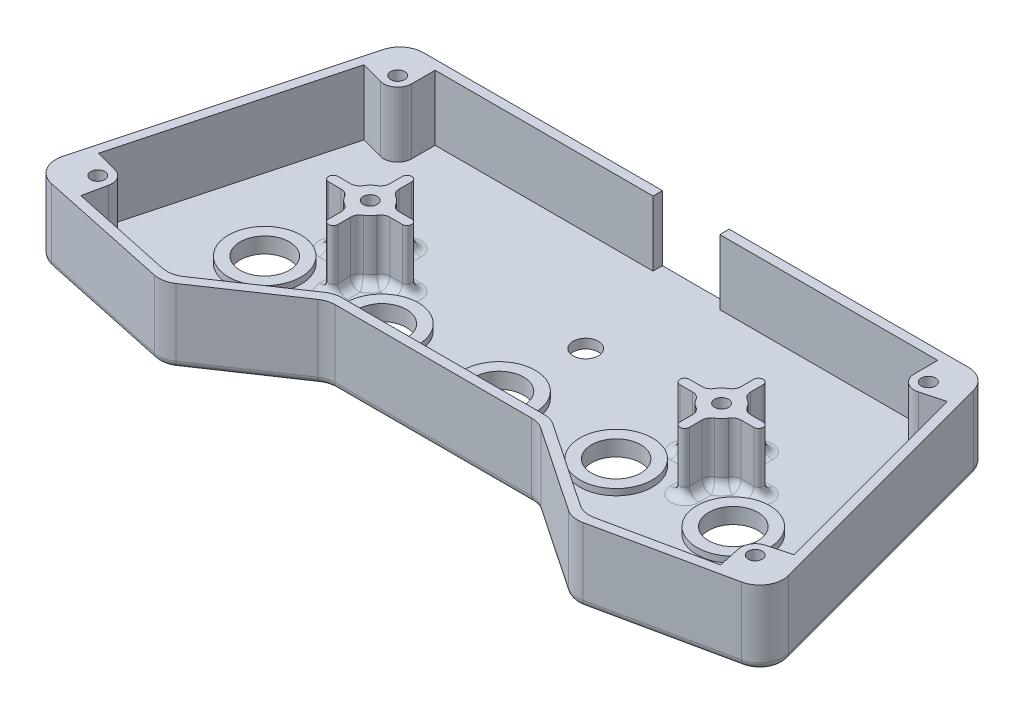
SolidWorks part; units mm, degrees
ref_plane "Front Plane" through (0, 0, 0) normal (0, 0, 1) x (1, 0, 0)
ref_plane "Top Plane" through (0, 0, 0) normal (0, 1, 0) x (1, 0, 0)
ref_plane "Right Plane" through (0, 0, 0) normal (1, 0, 0) x (0, 0, -1)
sketch "Sketch10" plane through (0, 0, 0) normal (0, 1, 0) x (1, 0, 0)
  line L0 (62, 32) -> (-62, 32)
  line L1 (-62, 32) -> (-78.8232, -30.7852)
  line L2 (-78.8232, -30.7852) -> (-43.6451, -38.2625)
  line L3 (-43.6451, -38.2625) -> (-22.5, -24)
  line L4 (-22.5, -24) -> (22.5, -24)
  line L5 (22.5, -24) -> (43.6451, -38.2625)
  line L6 (43.6451, -38.2625) -> (78.8232, -30.7852)
  line L7 (78.8232, -30.7852) -> (62, 32)
  line L8 (-50, -10) -> (-25, -10) construction
  line L9 (-25, -10) -> (0, -10) construction
  line L10 (0, -10) -> (25, -10) construction
  line L11 (25, -10) -> (50, -10) construction
  line L12 (-27, 0) -> (27, 0) construction
  line L13 (0, 0) -> (0, 32) construction
  line L14 (0, 0) -> (0, -24) construction
  line L15 (78.8232, -30.7852) -> (22.5, -24) construction
  line L16 (-22.5, -24) -> (-78.8232, -30.7852) construction
  circle A0 centre (50, -10) radius 5.25
  circle A2 centre (0, -10) radius 5.25
  circle A3 centre (25, -10) radius 5.25
  circle A5 centre (-50, -10) radius 5.25
  circle A6 centre (-25, -10) radius 5.25
  dimension "D1" = 10.5
  dimension "D2" = 25
  dimension "D3" = 65
  dimension "D4" = 124
  dimension "D5" = 10
  dimension "D6" = 105
  dimension "D7" = 56
  dimension "D8" = 45
  dimension "D9" = 32
  dimension "D10" = 34
  dimension "D11" = 12
extrude "Boss-Extrude5" add sketch "Sketch10" along normal blind 2 separate body contours L7 L0 L1 L2 L3 L4 L5 L6
sketch "Sketch11" plane through (0, 2, 0) normal (0, 1, 0) x (1, 0, 0)
  line L0 (-78.8232, -30.7852) -> (-62, 32)
  line L1 (-62, 32) -> (62, 32)
  line L2 (62, 32) -> (78.8232, -30.7852)
  line L3 (78.8232, -30.7852) -> (43.6451, -38.2625)
  line L4 (43.6451, -38.2625) -> (22.5, -24)
  line L5 (22.5, -24) -> (-22.5, -24)
  line L6 (-22.5, -24) -> (-43.6451, -38.2625)
  line L7 (-43.6451, -38.2625) -> (-78.8232, -30.7852)
  line L8 (-44.0596, -36.1297) -> (-76.3459, -29.2671)
  line L9 (-76.3459, -29.2671) -> (-60.4653, 30)
  line L10 (-60.4653, 30) -> (60.4653, 30)
  line L11 (60.4653, 30) -> (76.3459, -29.2671)
  line L12 (76.3459, -29.2671) -> (44.0596, -36.1297)
  line L13 (44.0596, -36.1297) -> (23.1115, -22)
  line L14 (23.1115, -22) -> (-23.1115, -22)
  line L15 (-23.1115, -22) -> (-44.0596, -36.1297)
  dimension "D1" = 2
extrude "Boss-Extrude7" add sketch "Sketch11" along direction (0, -1, 0) on the side of the normal offset from surface (13.875 mm away) 15.875 contours L0 L1 L2 L3 L4 L5 L6 L7
fillet "Fillet4" radius 5 16 edges at (62, 7.9375, -32) (78.8232, 7.9375, 30.7852) (43.6451, 7.9375, 38.2625) (22.5, 7.9375, 24) (-22.5, 7.9375, 24) (-43.6451, 7.9375, 38.2625) (-62, 7.9375, -32) (-78.8232, 7.9375, 30.7852) (76.3459, 8.9375, 29.2671) (60.4653, 8.9375, -30) (44.0596, 8.9375, 36.1297) (23.1115, 8.9375, 22) (-23.1115, 8.9375, 22) (-44.0596, 8.9375, 36.1297) (-76.3459, 8.9375, 29.2671) (-60.4653, 8.9375, -30)
fillet "Fillet5" radius 1.5 16 edges at (43.7275, 0, 37.8387) (32.8264, 0, 30.9653) (22.4332, 0, 24.2185) (0, 0, 24) (-22.4332, 0, 24.2185) (-32.8264, 0, 30.9653) (-43.7275, 0, 37.8387) (-59.6953, 0, 34.851) (-76.8931, 0, 29.6024) (-70.2263, 0, -1.2991) (-61.2072, 0, -30.9668) (0, 0, -32) (61.2072, 0, -30.9668) (70.2263, 0, -1.2991) (76.8931, 0, 29.6024) (59.6953, 0, 34.851)
sketch "Sketch12" plane through (0, 2, 0) normal (0, 1, 0) x (1, 0, 0)
  line L0 (-62.2348, 23.3963) -> (-57.4052, 22.1022)
  line L1 (-61.4583, 26.2941) -> (-74.9822, -24.1777) construction
  line L2 (-53.6287, 25) -> (-53.6287, 30)
  line L3 (56.6287, 30) -> (-56.6287, 30) construction
  line L4 (-53.6287, 30) -> (-56.6287, 30)
  line L5 (-61.4583, 26.2941) -> (-62.2348, 23.3963)
  line L6 (-74.9822, -24.1777) -> (-74.2058, -21.2799)
  line L7 (-74.2058, -21.2799) -> (-69.3761, -22.574)
  line L8 (-67.2181, -26.0955) -> (-68.2577, -30.9863)
  line L9 (-71.1921, -30.3625) -> (-46.1356, -35.6885) construction
  line L10 (-68.2577, -30.9863) -> (-71.1921, -30.3625)
  line L11 (0, 0) -> (0, 17.9434) construction
  line L12 (68.2577, -30.9863) -> (71.1921, -30.3625)
  line L13 (67.2181, -26.0955) -> (68.2577, -30.9863)
  line L14 (74.2058, -21.2799) -> (69.3761, -22.574)
  line L15 (74.9822, -24.1777) -> (74.2058, -21.2799)
  line L16 (61.4583, 26.2941) -> (62.2348, 23.3963)
  line L17 (53.6287, 30) -> (56.6287, 30)
  line L18 (53.6287, 25) -> (53.6287, 30)
  line L19 (62.2348, 23.3963) -> (57.4052, 22.1022)
  arc A0 (-57.4052, 22.1022) -> (-53.6287, 25) centre (-56.6287, 25) ccw
  arc A1 (-56.6287, 30) -> (-61.4583, 26.2941) centre (-56.6287, 25) ccw
  arc A2 (-69.3761, -22.574) -> (-67.2181, -26.0955) centre (-70.1526, -25.4718) cw
  arc A3 (-71.1921, -30.3625) -> (-74.9822, -24.1777) centre (-70.1526, -25.4718) cw
  circle A4 centre (-56.6287, 25) radius 1.5
  circle A5 centre (-70.1526, -25.4718) radius 1.5
  circle A6 centre (70.1526, -25.4718) radius 1.5
  circle A7 centre (56.6287, 25) radius 1.5
  arc A8 (71.1921, -30.3625) -> (74.9822, -24.1777) centre (70.1526, -25.4718) ccw
  arc A9 (69.3761, -22.574) -> (67.2181, -26.0955) centre (70.1526, -25.4718) ccw
  arc A10 (56.6287, 30) -> (61.4583, 26.2941) centre (56.6287, 25) cw
  arc A11 (57.4052, 22.1022) -> (53.6287, 25) centre (56.6287, 25) cw
  dimension "D1" = 3
  dimension "D2" = 1.5
extrude "Boss-Extrude8" add sketch "Sketch12" along normal up to surface (13.875 mm away) contours L0 A0 L2 L4 A1 L5
sketch "Sketch14" plane through (0, 0, -30) normal (0, 0, 1) x (1, 0, 0)
  line L0 (-53.6287, 15.875) -> (53.6287, 15.875) construction
  line L5 (0, 0) -> (0, 15.875) construction
  line L10 (-6.625, 15.03) -> (-6.625, 2.5) construction
  line L11 (-7.125, 15.875) -> (7.125, 15.875)
  line L12 (-7.125, 15.875) -> (-7.125, 2)
  line L13 (-7.125, 2) -> (7.125, 2)
  line L14 (7.125, 15.875) -> (7.125, 2)
  line L15 (53.6287, 2) -> (-53.6287, 2) construction
  dimension "D1" = 0.5
extrude "Cut-Extrude2" cut sketch "Sketch14" against normal through all
sketch "Sketch15" plane through (0, 0, 0) normal (0, -1, 0) x (1, 0, 0)
  line L0 (0, -8.5) -> (0, -30.5) construction
  line L1 (-58.1634, -30.5) -> (58.1634, -30.5) construction
  circle A0 centre (0, -8.5) radius 2.7
  dimension "D2" = 5.4
  dimension "D1" = 22
extrude "Cut-Extrude3" cut sketch "Sketch15" against normal through all contours A0
sketch "Sketch16" plane through (0, 2, 0) normal (0, 1, 0) x (1, 0, 0)
  circle A0 centre (25, -10) radius 7.75
  circle A1 centre (25, -10) radius 5.25
  circle A2 centre (0, -10) radius 7.75
  circle A3 centre (0, -10) radius 5.25
  circle A4 centre (-50, -10) radius 5.25
  circle A5 centre (-50, -10) radius 7.75
  circle A6 centre (-25, -10) radius 5.25
  circle A7 centre (-25, -10) radius 7.75
  circle A9 centre (-50, -10) radius 5.25 construction
  circle A10 centre (-25, -10) radius 5.25 construction
  circle A12 centre (25, -10) radius 5.25 construction
  circle A13 centre (0, -10) radius 5.25 construction
  circle A14 centre (50, -10) radius 7.75
  circle A15 centre (50, -10) radius 5.25
  circle A16 centre (50, -10) radius 5.25 construction
  dimension "D1" = 2.5
extrude "Boss-Extrude9" add sketch "Sketch16" along normal blind 1.35
sketch "Sketch17" plane through (0, 2, 0) normal (0, 1, 0) x (1, 0, 0)
  line L0 (-38.5, 3.873) -> (-38.5, 7.873)
  line L3 (-36.5, 7.873) -> (-36.5, 3.873)
  line L4 (-33.627, 1) -> (-29.627, 1)
  line L5 (-29.627, -1) -> (-33.627, -1)
  line L8 (-41.373, -1) -> (-45.373, -1)
  line L9 (-45.373, 1) -> (-41.373, 1)
  line L10 (-45.373, 0) -> (-37.5, 0) construction
  line L11 (-37.5, 0) -> (-29.627, 0) construction
  line L12 (-37.5, -1.5) -> (-37.5, 0) construction
  line L13 (-37.5, 7.873) -> (-37.5, 0) construction
  line L14 (-38.5, -3.873) -> (-38.5, -7.873)
  line L15 (-37.5, 0) -> (0, 0) construction
  line L16 (-36.5, -7.873) -> (-36.5, -3.873)
  line L17 (-37.5, -7.873) -> (-37.5, 0) construction
  arc A0 (-38.5, 3.873) -> (-41.373, 1) centre (-37.5, 0) ccw
  arc A3 (-38.5, 7.873) -> (-36.5, 7.873) centre (-37.5, 7.873) cw
  arc A4 (-29.627, 1) -> (-29.627, -1) centre (-29.627, 0) cw
  arc A6 (-45.373, -1) -> (-45.373, 1) centre (-45.373, 0) cw
  arc A7 (-33.627, 1) -> (-36.5, 3.873) centre (-37.5, 0) ccw
  arc A8 (-41.373, -1) -> (-38.5, -3.873) centre (-37.5, 0) ccw
  circle A10 centre (-37.5, 0) radius 1.5
  arc A11 (-38.5, -7.873) -> (-36.5, -7.873) centre (-37.5, -7.873) ccw
  arc A12 (-36.5, -3.873) -> (-33.627, -1) centre (-37.5, 0) ccw
  dimension "D1" = 37.5
  dimension "D4" = 8
  dimension "D5" = 3
  dimension "D2" = 2
  dimension "D3" = 4
extrude "PCB Mount Posts" add sketch "Sketch17" along normal offset from surface (12.875 mm away) 1 up to face at (0, 15.875, 7.9916)
fillet "Fillet6" radius 2 8 edges at (-41.373, 8.4375, -1) (-38.5, 8.4375, -3.873) (-36.5, 8.4375, -3.873) (-33.627, 8.4375, -1) (-33.627, 8.4375, 1) (-36.5, 8.4375, 3.873) (-38.5, 8.4375, 3.873) (-41.373, 8.4375, 1)
mirror "Mirror1" about plane through (0, 0, 0) normal (1, 0, 0) of "Fillet6", "Boss-Extrude9", "PCB Mount Posts"
sketch "Sketch20" plane through (0, 0, 0) normal (0, -1, 0) x (1, 0, 0)
  line L0 (12.7379, 2) -> (-12.7379, 2) construction
  line L1 (0, 10) -> (0, 2) construction
  circle A0 centre (0, 10) radius 5.25 construction
  text T0 "RESET\r\n" font "Arial" height 5
  dimension "D1" = 8
extrude "Reset" cut sketch "Sketch20" against normal blind 0.5
sketch "Sketch21" plane through (0, 0, 0) normal (0, -1, 0) x (1, 0, 0)
  line L0 (27.3094, -5) -> (27.3094, 3)
  line L1 (27.3094, 3) -> (20.3812, -1)
  line L2 (20.3812, -1) -> (27.3094, -5)
  line L3 (-25, 10) -> (-25, -1) construction
  line L4 (-21.5, -5) -> (-23.5, -5)
  line L5 (-21.5, -5) -> (-21.5, 3)
  line L6 (-21.5, 3) -> (-23.5, 3)
  line L7 (-23.5, -5) -> (-23.5, 3)
  line L8 (-26.5, -5) -> (-28.5, -5)
  line L9 (-26.5, -5) -> (-26.5, 3)
  line L10 (-26.5, 3) -> (-28.5, 3)
  line L11 (-28.5, -5) -> (-28.5, 3)
  line L12 (-25, -1) -> (-26.5, -1) construction
  line L13 (-25, -1) -> (-23.5, -1) construction
  line L14 (20.3812, -1) -> (-21.5, -1) construction
  line L15 (27.3094, -1) -> (25, -1) construction
  line L16 (25, -1) -> (23.8453, -3) construction
  line L17 (25, -1) -> (23.8453, 1) construction
  line L18 (25, 10) -> (25, -1) construction
  line L22 (22.8812, -1) -> (26.0594, -2.8349)
  line L23 (26.0594, -2.8349) -> (26.0594, 0.8349)
  line L24 (26.0594, 0.8349) -> (22.8812, -1)
  circle A0 centre (-25, 10) radius 5.25 construction
  dimension "D1" = 3
  dimension "D2" = 11
  dimension "D3" = 8
  dimension "D4" = 2
  dimension "D5" = 1.25
extrude "Cut-Extrude4" cut sketch "Sketch21" against normal blind 0.5
fillet "Fillet7" radius 2 48 edges at (-46.373, 2, 0) (-44.0346, 2, 1) (-37.5, 2, 8.873) (-36.5, 2, 6.5346) (-28.627, 2, 0) (-30.9654, 2, -1) (-37.5, 2, -8.873) (-38.5, 2, -6.5346) (-30.9654, 2, 1) (-40.3284, 2, -2.8284) (-36.5, 2, -6.5346) (-34.6716, 2, -2.8284) (-34.6716, 2, 2.8284) (-38.5, 2, 6.5346) (-40.3284, 2, 2.8284) (-44.0346, 2, -1) (-33.3038, 2, -1.2679) (-36.2321, 2, -4.1962) (-38.7679, 2, -4.1962) (-41.6962, 2, -1.2679) (-41.6962, 2, 1.2679) (-38.7679, 2, 4.1962) (-36.2321, 2, 4.1962) (-33.3038, 2, 1.2679) (46.373, 2, 0) (44.0346, 2, 1) (37.5, 2, 8.873) (36.5, 2, 6.5346) (28.627, 2, 0) (30.9654, 2, -1) (37.5, 2, -8.873) (38.5, 2, -6.5346) (34.6716, 2, 2.8284) (40.3284, 2, -2.8284) (44.0346, 2, -1) (40.3284, 2, 2.8284) (38.5, 2, 6.5346) (30.9654, 2, 1) (34.6716, 2, -2.8284) (36.5, 2, -6.5346) (33.3038, 2, -1.2679) (36.2321, 2, -4.1962) (38.7679, 2, -4.1962) (41.6962, 2, -1.2679) (41.6962, 2, 1.2679) (38.7679, 2, 4.1962) (36.2321, 2, 4.1962) (33.3038, 2, 1.2679)
equation "\"TextAngle\"= 65"
equation "\"TextFromCircle\"=8"
